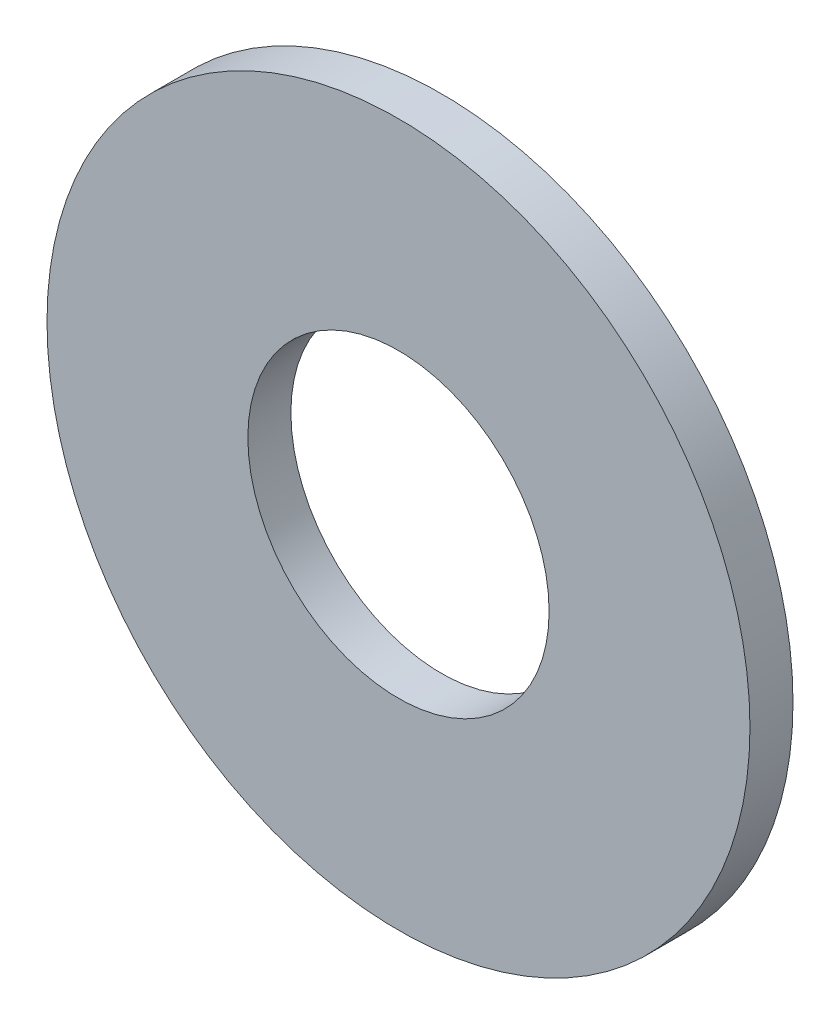
SolidWorks part; units mm, degrees
ref_plane "Plan de face" through (0, 0, 0) normal (0, 0, 1) x (1, 0, 0)
ref_plane "Plan de dessus" through (0, 0, 0) normal (0, 1, 0) x (1, 0, 0)
ref_plane "Plan de droite" through (0, 0, 0) normal (1, 0, 0) x (0, 0, -1)
sketch "Esquisse1" plane through (0, 0, 0) normal (0, 0, 1) x (1, 0, 0)
  circle A0 centre (0, 0) radius 2.45
  circle A1 centre (0, 0) radius 1.05
  dimension "D1" = 4.9
  dimension "D2" = 2.1
extrude "Boss.-Extru.1" add sketch "Esquisse1" along normal blind 0.3
